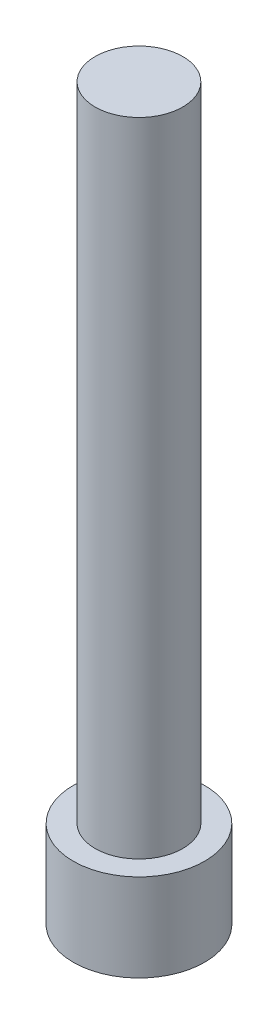
SolidWorks part; units mm, degrees
material "灰铸铁"
ref_plane "前视基准面" through (0, 0, 0) normal (0, 0, 1) x (1, 0, 0)
ref_plane "上视基准面" through (0, 0, 0) normal (0, 1, 0) x (1, 0, 0)
ref_plane "右视基准面" through (0, 0, 0) normal (1, 0, 0) x (0, 0, -1)
other "Configuration Table"
sketch "草图1" plane through (0, 0, 0) normal (0, 1, 0) x (1, 0, 0)
  circle A0 centre (0, 0) radius 2.25
  dimension "D1" = 4.5
extrude "凸台-拉伸1" add sketch "草图1" along normal blind 3
sketch "草图2" plane through (0, 3, 0) normal (0, 1, 0) x (1, 0, 0)
  circle A0 centre (0, 0) radius 1.5
  dimension "D1" = 3
extrude "凸台-拉伸2" add sketch "草图2" along normal blind 22
sketch "草图3" plane through (0, 0, 0) normal (0, -1, 0) x (1, 0, 0)
  line L1 (0.75, 1.299) -> (-0.75, 1.299)
  line L2 (-0.75, 1.299) -> (-1.5, 0)
  line L3 (-1.5, 0) -> (-0.75, -1.299)
  line L4 (-0.75, -1.299) -> (0.75, -1.299)
  line L5 (0.75, -1.299) -> (1.5, 0)
  line L6 (1.5, 0) -> (0.75, 1.299)
  circle A0 centre (0, 0) radius 1.299 construction
  dimension "D1" = 1.5
extrude "切除-拉伸1" cut sketch "草图3" against normal blind 2
fillet "圆角1" radius 0.1 6 edges at (0, 0, -1.299) (1.125, 0, -0.6495) (1.125, 0, 0.6495) (0, 0, 1.299) (-1.125, 0, -0.6495) (-1.125, 0, 0.6495)
